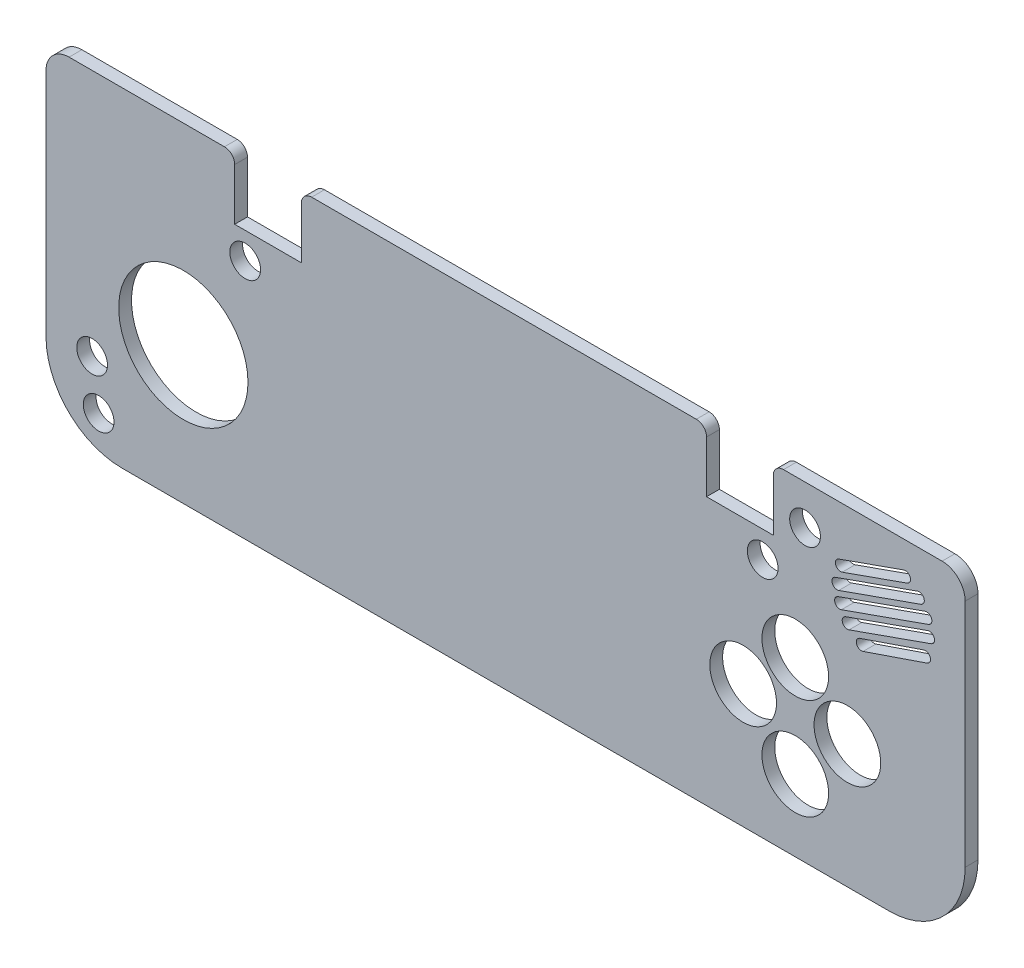
SolidWorks part; units mm, degrees
ref_plane "Plan de face" through (0, 0, 0) normal (0, 0, 1) x (1, 0, 0)
ref_plane "Plan de dessus" through (0, 0, 0) normal (0, 1, 0) x (1, 0, 0)
ref_plane "Plan de droite" through (0, 0, 0) normal (1, 0, 0) x (0, 0, -1)
sketch "Esquisse20" plane through (0, 0, 0) normal (0, 0, 1) x (1, 0, 0)
  line L1 (14.8, -2) -> (164.37, -2)
  line L2 (0, 12.8) -> (0, 57.73)
  line L3 (4.5, 62.23) -> (174.67, 62.23)
  line L4 (179.17, 12.8) -> (179.17, 57.73)
  arc A0 (0, 57.73) -> (4.5, 62.23) centre (4.5, 57.73) cw
  arc A1 (174.67, 62.23) -> (179.17, 57.73) centre (174.67, 57.73) cw
  arc A2 (164.37, -2) -> (179.17, 12.8) centre (164.37, 12.8) ccw
  arc A3 (14.8, -2) -> (0, 12.8) centre (14.8, 12.8) cw
  point P7 (0, 62.23)
  point P10 (179.17, 62.23)
  point P14 (179.17, -2)
  point P17 (0, -2)
extrude "Boss.-Extru.1" add sketch "Esquisse20" along normal blind 2.5
sketch "Esquisse22" plane through (0, 0, 2.5) normal (0, 0, 1) x (1, 0, 0)
  line L0 (14.8, -2) -> (164.37, -2) construction
  line L1 (0, 57.73) -> (0, 12.8) construction
  circle A0 centre (26.77, 24.77) radius 12.6
  dimension "D1" = 26.77
  dimension "D2" = 26.77
extrude "Enlèv. mat.-Extru.1" cut sketch "Esquisse22" against normal blind 2.5
sketch "Esquisse23" plane through (0, 0, 2.5) normal (0, 0, 1) x (1, 0, 0)
  line L0 (14.8, -2) -> (164.37, -2) construction
  line L1 (0, 57.73) -> (0, 12.8) construction
  circle A0 centre (8.99, 13.97) radius 3
  dimension "D1" = 15.97
  dimension "D2" = 8.99
extrude "Enlèv. mat.-Extru.2" cut sketch "Esquisse23" against normal blind 2.5
sketch "Esquisse24" plane through (0, 0, 2.5) normal (0, 0, 1) x (1, 0, 0)
  line L0 (36.78, 58.87) -> (49.78, 50.15)
  line L1 (36.78, 58.87) -> (49.78, 58.87)
  line L2 (36.78, 58.87) -> (36.78, 50.15)
  line L3 (36.78, 50.15) -> (49.78, 50.15)
  line L4 (49.78, 58.87) -> (49.78, 50.15)
  line L6 (0, 57.73) -> (0, 12.8) construction
  line L7 (174.67, 62.23) -> (4.5, 62.23) construction
  point P4 (43.28, 54.51)
  dimension "D1" = 13
  dimension "D2" = 8.72
  dimension "D3" = 43.28
  dimension "D4" = 7.72
extrude "Enlèv. mat.-Extru.3" cut sketch "Esquisse24" against normal blind 2.5 contours L2 L3 L0 | L4 L1 L0
sketch "Esquisse25" plane through (0, 0, 2.5) normal (0, 0, 1) x (1, 0, 0)
  line L0 (49.78, 58.87) -> (36.78, 58.87)
  line L1 (49.78, 58.87) -> (49.78, 62.2418)
  line L2 (36.78, 58.87) -> (36.78, 62.2418)
  line L3 (49.78, 62.2418) -> (36.78, 62.2418)
extrude "Enlèv. mat.-Extru.4" cut sketch "Esquisse25" against normal blind 2.5
fillet "Congé1" radius 2 2 edges at (49.78, 62.23, 1.25) (36.78, 62.23, 1.25)
sketch "Esquisse26" plane through (0, 0, 2.5) normal (0, 0, 1) x (1, 0, 0)
  line L0 (179.17, 12.8) -> (179.17, 57.73) construction
  line L1 (174.67, 62.23) -> (51.78, 62.23) construction
  circle A1 centre (156.21, 22.13) radius 6.5
  dimension "D2" = 22.96
  dimension "D3" = 40.1
sketch "Esquisse27" plane through (0, 0, 2.5) normal (0, 0, 1) x (1, 0, 0)
  line L0 (179.17, 12.8) -> (179.17, 57.73) construction
  line L1 (174.67, 62.23) -> (51.78, 62.23) construction
  circle A0 centre (146.05, 11.97) radius 6.5
  circle A1 centre (135.89, 22.13) radius 6.5
  circle A2 centre (146.05, 31.65) radius 6.5
  dimension "D1" = 33.12
  dimension "D2" = 43.28
  dimension "D3" = 33.12
  dimension "D4" = 30.58
  dimension "D5" = 40.1
  dimension "D6" = 50.26
extrude "Enlèv. mat.-Extru.5" cut sketch "Esquisse26" against normal blind 2.5
extrude "Enlèv. mat.-Extru.6" cut sketch "Esquisse27" against normal blind 2.5
sketch "Esquisse30" plane through (0, 0, 2.5) normal (0, 0, 1) x (1, 0, 0)
  line L0 (128.76, 58.87) -> (141.76, 50.15)
  line L1 (128.76, 58.87) -> (141.76, 58.87)
  line L2 (128.76, 58.87) -> (128.76, 50.15)
  line L3 (128.76, 50.15) -> (141.76, 50.15)
  line L4 (141.76, 58.87) -> (141.76, 50.15)
  line L5 (141.76, 58.87) -> (128.76, 50.15)
  line L6 (174.67, 62.23) -> (51.78, 62.23) construction
  line L7 (179.17, 12.8) -> (179.17, 57.73) construction
  line L8 (141.76, 58.87) -> (128.76, 58.87)
  line L9 (141.76, 58.87) -> (141.76, 62.2543)
  line L10 (128.76, 58.87) -> (128.76, 62.2543)
  line L11 (141.76, 62.2543) -> (128.76, 62.2543)
  point P4 (135.26, 54.51)
  line M7 (174.67, 62.23) -> (51.78, 62.23)
  dimension "D1" = 13
  dimension "D2" = 8.72
  dimension "D3" = 7.72
  dimension "D4" = 43.91
extrude "Enlèv. mat.-Extru.7" cut sketch "Esquisse30" against normal blind 2.5 contours L10 L1 L9 M7 | L5 L1 L0 | L5 L0 L2 | L0 L5 L3 | L4 L5 L0
fillet "Congé2" radius 2 2 edges at (141.76, 62.23, 1.25) (128.76, 62.23, 1.25)
sketch "Esquisse31" plane through (0, 0, 2.5) normal (0, 0, 1) x (1, 0, 0)
  line L0 (126.76, 62.23) -> (51.78, 62.23) construction
  line L1 (179.17, 12.8) -> (179.17, 57.73) construction
  circle A0 centre (147.96, 54.51) radius 3
  circle A1 centre (139.7, 44.99) radius 3
  dimension "D1" = 7.72
  dimension "D3" = 17.24
  dimension "D2" = 31.21
  dimension "D4" = 39.47
extrude "Enlèv. mat.-Extru.8" cut sketch "Esquisse31" against normal blind 2.5
sketch "Esquisse32" plane through (0, 0, 2.5) normal (0, 0, 1) x (1, 0, 0)
  line L0 (179.17, 12.8) -> (179.17, 57.73) construction
  line L1 (174.67, 62.23) -> (143.76, 62.23) construction
  line L2 (171.6853, 51.16) -> (154.7147, 45.16) construction
  line L3 (172.0186, 50.2172) -> (155.0481, 44.2172)
  line L4 (171.3519, 52.1028) -> (154.3814, 46.1028)
  line L5 (154.2, 48.16) -> (170.2, 53.8169) construction
  line L6 (153.8667, 49.1028) -> (169.8667, 54.7597)
  line L7 (154.5333, 47.2172) -> (170.5333, 52.874)
  line L8 (154.8754, 51.5808) -> (167.5246, 56.0529) construction
  line L9 (154.5421, 52.5236) -> (167.1912, 56.9957)
  line L10 (155.2088, 50.638) -> (167.8579, 55.1101)
  line L11 (156.2, 42.5031) -> (172.2, 48.16) construction
  line L12 (155.8667, 43.446) -> (171.8667, 49.1028)
  line L13 (156.5333, 41.5603) -> (172.5333, 47.2172)
  line L14 (158.9416, 40.2312) -> (171.4222, 44.5) construction
  line L17 (158.6179, 41.1774) -> (171.0986, 45.4462)
  line L18 (159.2652, 39.285) -> (171.7458, 43.5538)
  circle A0 centre (163.2, 48.16) radius 10
  circle A1 centre (163.2, 48.16) radius 9
  arc A2 (172.0186, 50.2172) -> (171.3519, 52.1028) centre (171.6853, 51.16) ccw
  arc A3 (154.3814, 46.1028) -> (155.0481, 44.2172) centre (154.7147, 45.16) ccw
  arc A4 (153.8667, 49.1028) -> (154.5333, 47.2172) centre (154.2, 48.16) ccw
  arc A5 (170.5333, 52.874) -> (169.8667, 54.7597) centre (170.2, 53.8169) ccw
  arc A6 (154.5421, 52.5236) -> (155.2088, 50.638) centre (154.8754, 51.5808) ccw
  arc A7 (167.8579, 55.1101) -> (167.1912, 56.9957) centre (167.5246, 56.0529) ccw
  arc A8 (155.8667, 43.446) -> (156.5333, 41.5603) centre (156.2, 42.5031) ccw
  arc A9 (172.5333, 47.2172) -> (171.8667, 49.1028) centre (172.2, 48.16) ccw
  arc A12 (158.6179, 41.1774) -> (159.2652, 39.285) centre (158.9416, 40.2312) ccw
  arc A13 (171.7458, 43.5538) -> (171.0986, 45.4462) centre (171.4222, 44.5) ccw
  point P9 (163.2, 48.16)
  point P16 (162.2, 50.9884)
  point P23 (161.2, 53.8169)
  point P30 (164.2, 45.3316)
  point P37 (165.1819, 42.3656)
  dimension "D1" = 15.97
  dimension "D3" = 0.589
  dimension "D2" = 14.07
  dimension "D4" = 3
  dimension "D5" = 3
  dimension "D6" = 3
extrude "Enlèv. mat.-Extru.9" cut sketch "Esquisse32" against normal blind 2.5 contours L10 A7 L9 A6 | L7 A5 L6 A4 | L3 A3 L4 A2 | L13 A9 L12 A8 | L18 A13 L17 A12
sketch "Esquisse33" plane through (0, 0, 2.5) normal (0, 0, 1) x (1, 0, 0)
  line L0 (0, 57.73) -> (0, 12.8) construction
  line L1 (34.78, 62.23) -> (4.5, 62.23) construction
  circle A0 centre (38.83, 44.99) radius 3
  dimension "D1" = 38.83
  dimension "D2" = 17.24
extrude "Enlèv. mat.-Extru.10" cut sketch "Esquisse33" against normal blind 10
sketch "Esquisse34" plane through (0, 0, 2.5) normal (0, 0, 1) x (1, 0, 0)
  line L0 (14.8, -2) -> (164.37, -2) construction
  line L1 (0, 57.73) -> (0, 12.8) construction
  circle A0 centre (10.26, 4.99) radius 3
  dimension "D1" = 6.99
  dimension "D2" = 10.26
extrude "Enlèv. mat.-Extru.11" cut sketch "Esquisse34" against normal blind 10
